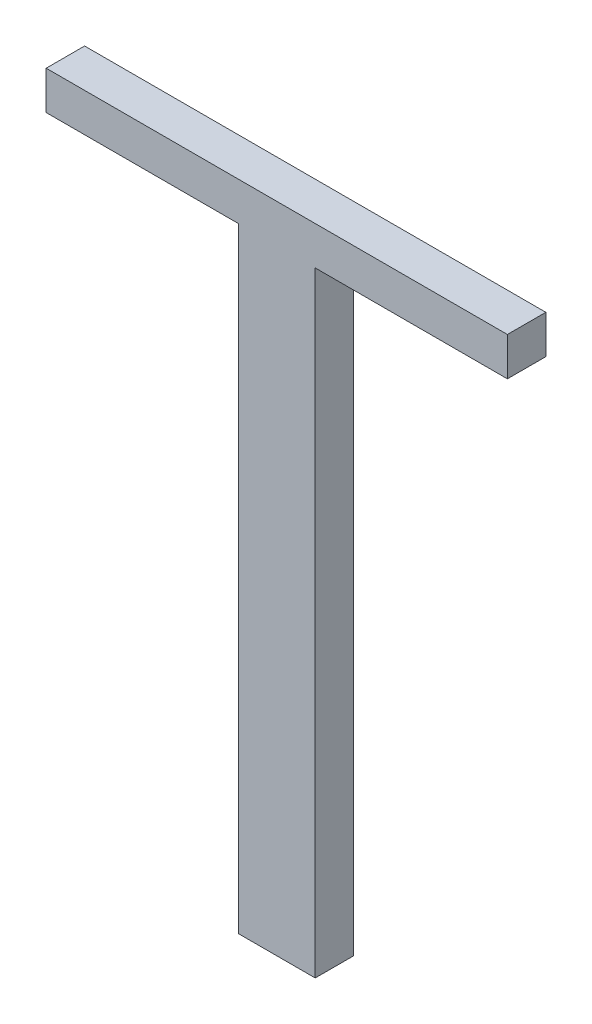
SolidWorks part; units mm, degrees
material "ABS"
ref_plane "Front" through (0, 0, 0) normal (0, 0, 1) x (1, 0, 0)
ref_plane "Top" through (0, 0, 0) normal (0, 1, 0) x (1, 0, 0)
ref_plane "Right" through (0, 0, 0) normal (1, 0, 0) x (0, 0, -1)
sketch "Sketch1" plane through (0, 0, 0) normal (0, 0, 1) x (1, 0, 0)
  line L0 (10, 80) -> (35, 80)
  line L1 (0, 0) -> (10, 0)
  line L2 (0, 0) -> (0, 80)
  line L4 (10, 0) -> (10, 80)
  line L5 (-25, 80) -> (0, 80)
  line L6 (-25, 80) -> (-25, 85)
  line L7 (-25, 85) -> (35, 85)
  line L8 (35, 80) -> (35, 85)
  dimension "D1" = 10
  dimension "D2" = 60
  dimension "D3" = 5
  dimension "D4" = 80
extrude "Boss-Extrude1" add sketch "Sketch1" along normal blind 5
